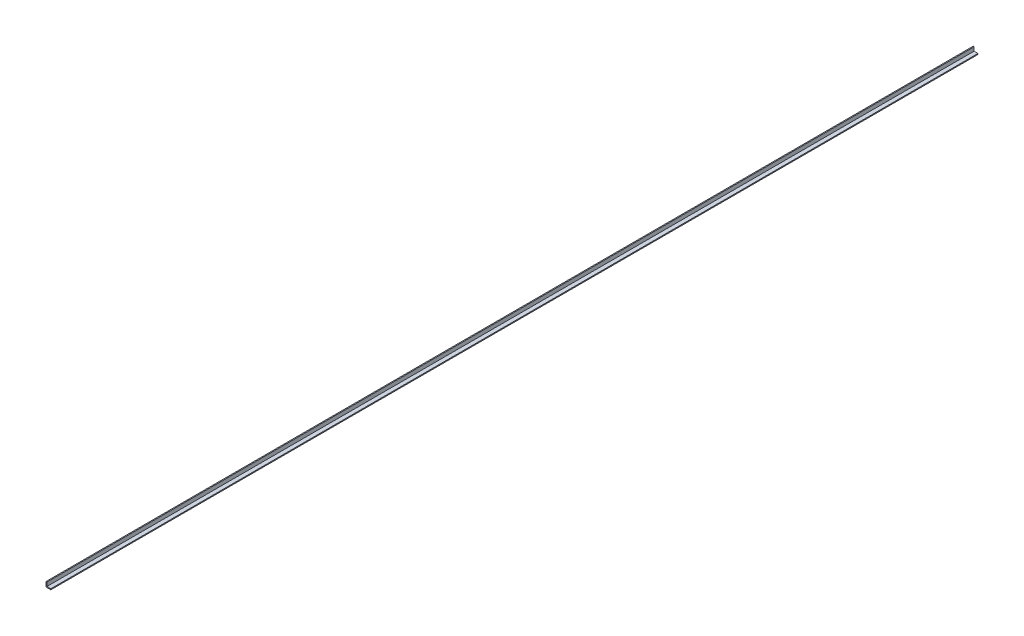
SolidWorks part; units mm, degrees
material "ASTM A36 Acero"
ref_plane "Alzado" through (0, 0, 0) normal (0, 0, 1) x (1, 0, 0)
ref_plane "Planta" through (0, 0, 0) normal (0, 1, 0) x (1, 0, 0)
ref_plane "Vista lateral" through (0, 0, 0) normal (1, 0, 0) x (0, 0, -1)
sketch "Croquis1" plane through (0, 0, 0) normal (0, 0, 1) x (1, 0, 0)
  line L0 (0, 31.75) -> (0, 0)
  line L1 (0, 0) -> (31.75, 0)
  line L2 (31.75, 0) -> (31.75, 6.35)
  line L3 (31.75, 6.35) -> (6.35, 6.35)
  line L4 (6.35, 6.35) -> (6.35, 31.75)
  line L5 (6.35, 31.75) -> (0, 31.75)
  dimension "D1" = 6.35
  dimension "D2" = 31.75
extrude "Saliente-Extruir1" add sketch "Croquis1" against normal blind 6100
